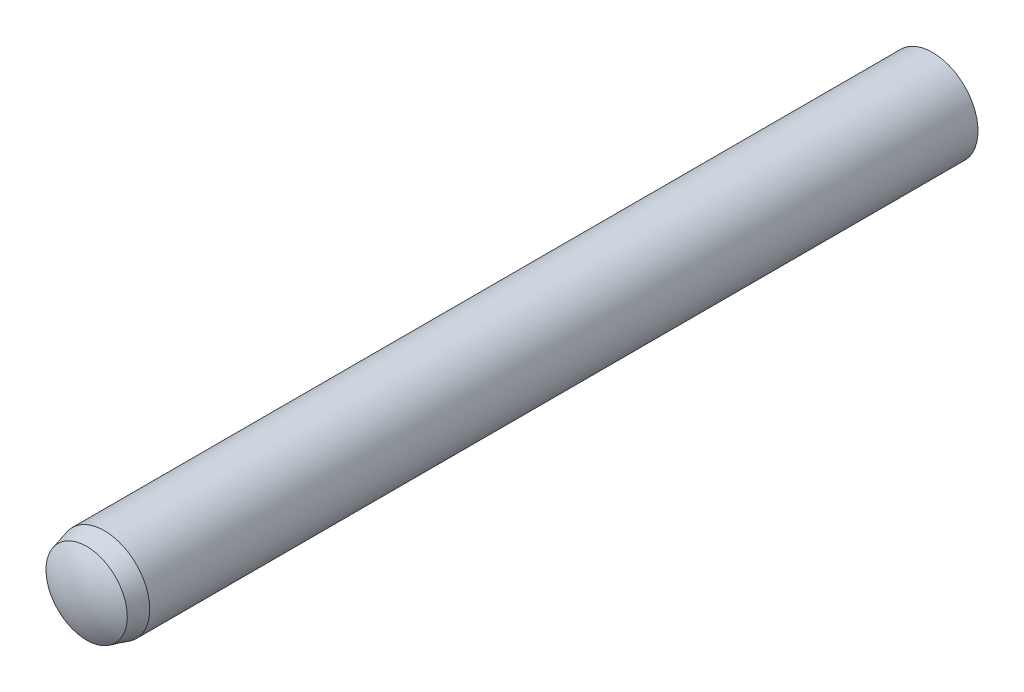
SolidWorks part; units mm, degrees
material "Alloy Steel"
ref_plane "Front Plane" through (0, 0, 0) normal (0, 0, 1) x (1, 0, 0)
ref_plane "Top Plane" through (0, 0, 0) normal (0, 1, 0) x (1, 0, 0)
ref_plane "Right Plane" through (0, 0, 0) normal (1, 0, 0) x (0, 0, -1)
sketch "Sketch1" plane through (0, 0, 0) normal (0, 0, 1) x (1, 0, 0)
  circle A0 centre (0, 0) radius 1.25
  point P3 (0, 1.25)
  dimension "Diameter" = 2.5
sketch "Sketch2" plane through (0, 0, 0) normal (1, 0, 0) x (0, 0, -1)
  line L0 (-12, 0) -> (12, 0) construction
  line L1 (-12, 0) -> (-12, 1.25) construction
  line L2 (-12, 1.25) -> (12, 1.25)
  line L3 (12, 1.25) -> (12, 0) construction
  line L4 (-11.675, 1.1194) -> (-11.1875, 1.25)
  arc A0 (-12, 0) -> (-11.675, 1.1194) centre (-9.9098, 0) cw
  arc A1 (12, 0) -> (11.625, 1.25) centre (9.7292, 0) ccw
  point P2 (0, 0)
  point P11 (-9.5, 0)
  point P13 (9.5, 0)
  dimension "Length" = 24
  dimension "D1" = 15
  dimension "D2" = 0.375
  dimension "D3" = 0.8125
  dimension "D4" = 0.4875
  dimension "D5" = 2.5
  dimension "D6" = 2.5
sketch "Sketch3" plane through (0, 0, 0) normal (1, 0, 0) x (0, 0, -1)
  line L0 (-12, 0) -> (12, 0) construction
  line L1 (-11.675, 1.1194) -> (-11.1875, 1.25) construction
  line L2 (-12, 0) -> (12, 0)
  line L3 (-11.675, 1.1194) -> (-11.1875, 1.25)
  line L4 (-11.1875, 1.25) -> (11.625, 1.25)
  arc A0 (12, 0) -> (11.625, 1.25) centre (9.7292, 0) ccw construction
  arc A1 (-11.675, 1.1194) -> (-12, 0) centre (-9.9098, 0) ccw construction
  arc A2 (12, 0) -> (11.625, 1.25) centre (9.7292, 0) ccw
  arc A3 (-11.675, 1.1194) -> (-12, 0) centre (-9.9098, 0) ccw
revolve "Revolve1" add sketch "Sketch3" angle 360 about L2
equation "\"D2@Sketch2\" = \"Diameter@Sketch1\" * .15"
equation "\"D3@Sketch2\" = \"Diameter@Sketch1\" * .325"
equation "\"D4@Sketch2\" = \"D3@Sketch2\" * .6"
equation "\"D5@Sketch2\"=\"Diameter@Sketch1\""
equation "\"D6@Sketch2\"=\"D5@sketch2\""
